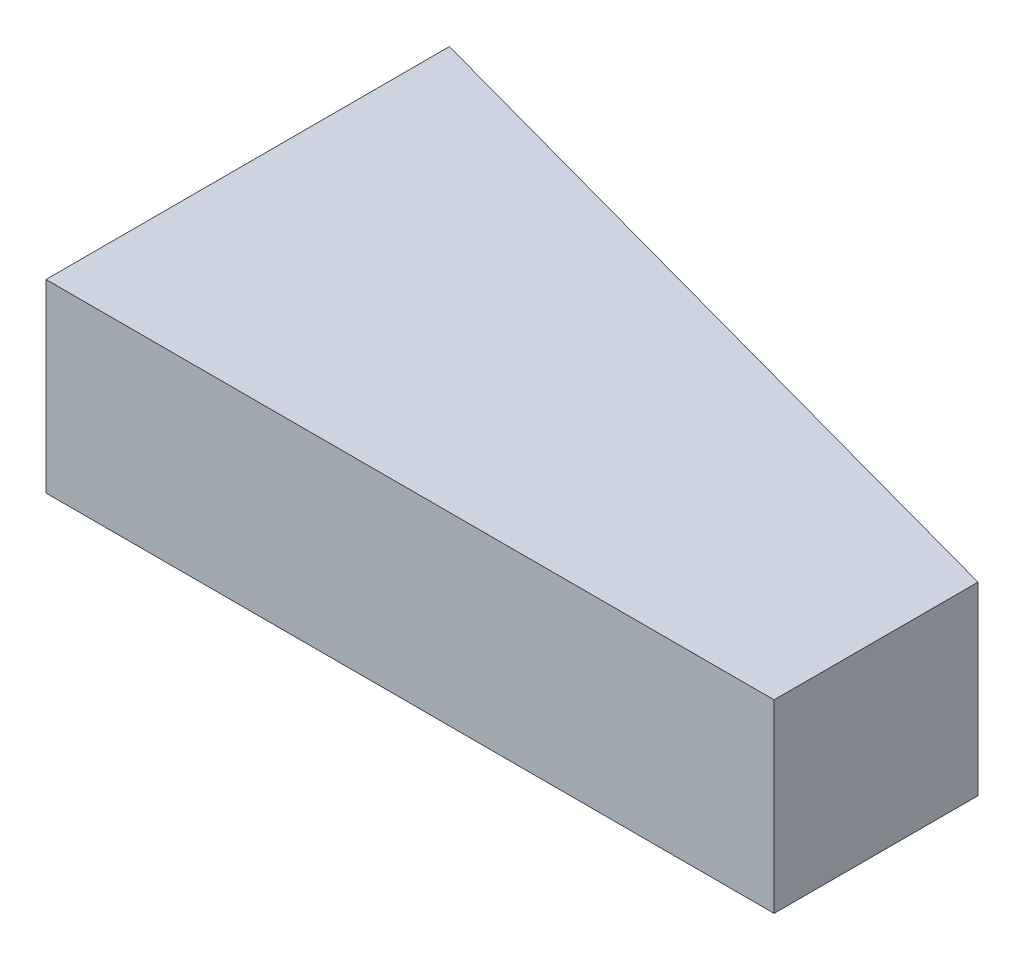
SolidWorks part; units mm, degrees
ref_plane "Front Plane" through (0, 0, 0) normal (0, 0, 1) x (1, 0, 0)
ref_plane "Top Plane" through (0, 0, 0) normal (0, 1, 0) x (1, 0, 0)
ref_plane "Right Plane" through (0, 0, 0) normal (1, 0, 0) x (0, 0, -1)
sketch "Sketch2" plane through (0, 0, 0) normal (0, 1, 0) x (1, 0, 0)
  line L0 (0, 0) -> (0, 55.4)
  line L2 (100, 0) -> (0, 0)
  line L3 (100, 0) -> (100, 28)
  line L4 (100, 28) -> (0, 55.4)
  dimension "D1" = 55.4
  dimension "D2" = 28
  dimension "D3" = 100
extrude "Boss-Extrude1" add sketch "Sketch2" along normal blind 25.4
